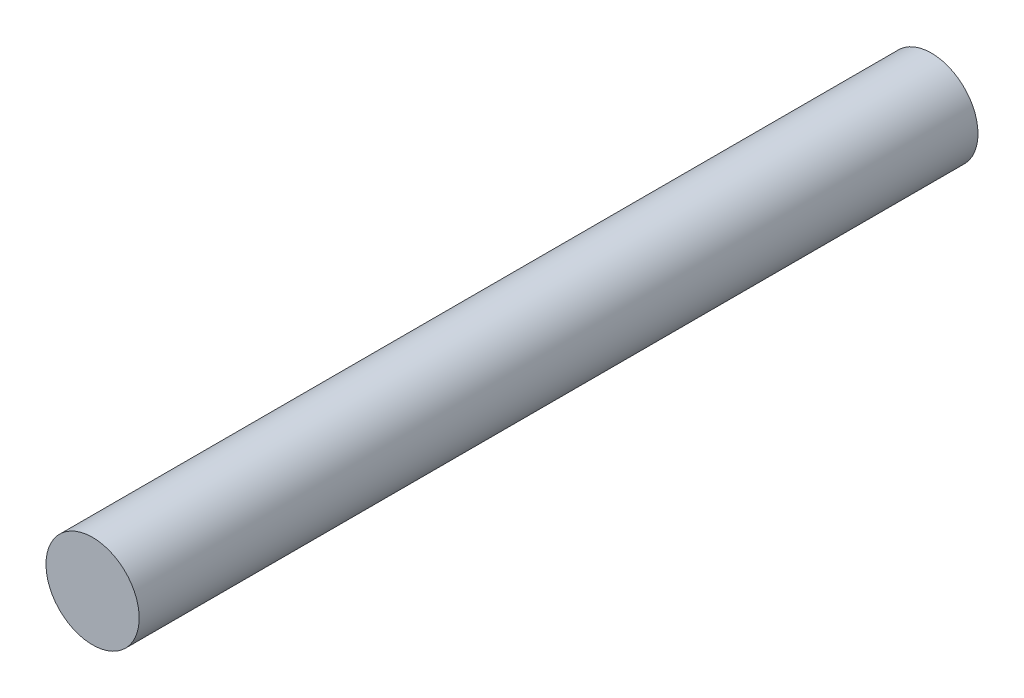
SolidWorks part; units mm, degrees
ref_plane "前视基准面" through (0, 0, 0) normal (0, 0, 1) x (1, 0, 0)
ref_plane "上视基准面" through (0, 0, 0) normal (0, 1, 0) x (1, 0, 0)
ref_plane "右视基准面" through (0, 0, 0) normal (1, 0, 0) x (0, 0, -1)
sketch "草图1" plane through (0, 0, 0) normal (0, 0, 1) x (1, 0, 0)
  circle A0 centre (0, 0) radius 5
  dimension "D1" = 10
extrude "凸台-拉伸1" add sketch "草图1" along normal up to surface (90 mm away)
